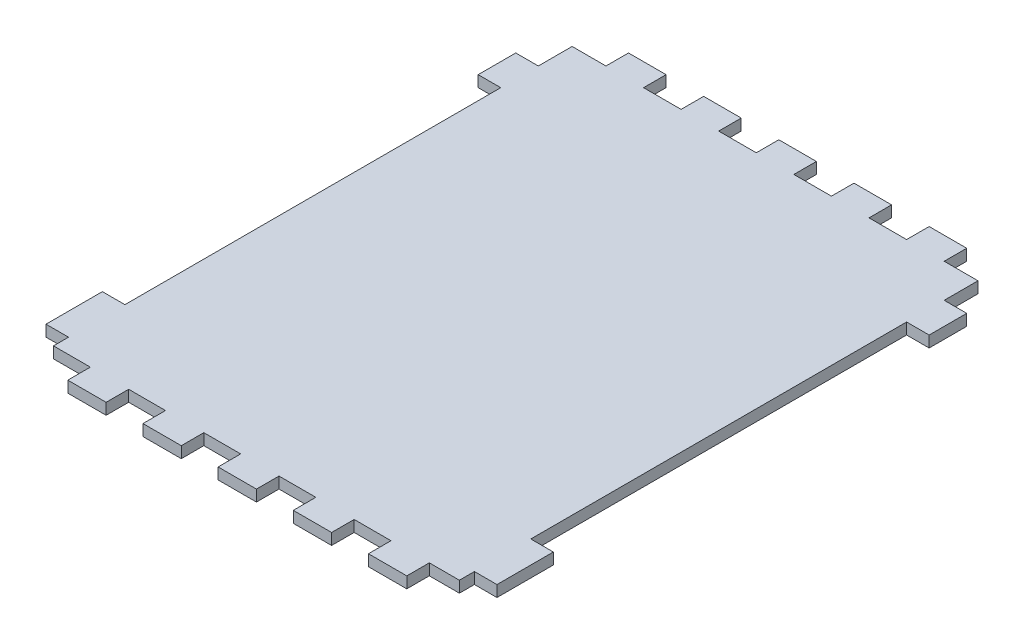
SolidWorks part; units mm, degrees
ref_plane "Спереди" through (0, 0, 0) normal (0, 0, 1) x (1, 0, 0)
ref_plane "Сверху" through (0, 0, 0) normal (0, 1, 0) x (1, 0, 0)
ref_plane "Справа" through (0, 0, 0) normal (1, 0, 0) x (0, 0, -1)
other "Configuration Table"
sketch "Эскиз1" plane through (0, 0, 0) normal (0, 1, 0) x (1, 0, 0)
  line L1 (0, 0) -> (108, 0)
  line L2 (0, 0) -> (0, -138)
  line L3 (0, -138) -> (108, -138)
  line L4 (108, 0) -> (108, -138)
  dimension "D1" = 138
  dimension "D2" = 108
extrude "Бобышка-Вытянуть1" add sketch "Эскиз1" along normal blind 4
sketch "Эскиз3" plane through (0, 0, 0) normal (0, -1, 0) x (1, 0, 0)
  line L1 (0, 138) -> (108, 138)
  line L2 (0, 138) -> (0, 0)
  line L3 (0, 0) -> (108, 0)
  line L4 (108, 138) -> (108, 0)
extrude "Вырез-Вытянуть2" cut sketch "Эскиз3" against normal blind 1
sketch "Эскиз4" plane through (0, 0, 138) normal (0, 0, 1) x (1, 0, 0)
  line L0 (0, 4) -> (108, 4) construction
  line L1 (10, 4) -> (20, 4)
  line L2 (10, 4) -> (10, 1)
  line L3 (10, 1) -> (20, 1)
  line L4 (20, 4) -> (20, 1)
  line L5 (108, 1) -> (0, 1) construction
  line L6 (0, 4) -> (0, 1) construction
  line L7 (30, 4) -> (30, 1)
  line L8 (30, 4) -> (40, 4)
  line L9 (40, 4) -> (40, 1)
  line L10 (30, 1) -> (40, 1)
  line L11 (50, 4) -> (50, 1)
  line L12 (50, 4) -> (60, 4)
  line L13 (60, 4) -> (60, 1)
  line L14 (50, 1) -> (60, 1)
  line L15 (70, 4) -> (70, 1)
  line L16 (70, 4) -> (80, 4)
  line L17 (80, 4) -> (80, 1)
  line L18 (70, 1) -> (80, 1)
  line L19 (90, 4) -> (90, 1)
  line L20 (90, 4) -> (100, 4)
  line L21 (100, 4) -> (100, 1)
  line L22 (90, 1) -> (100, 1)
  dimension "D1" = 10
  dimension "D2" = 10
  dimension "D3" = 5
extrude "Бобышка-Вытянуть2" add sketch "Эскиз4" along normal blind 6
sketch "Эскиз5" plane through (0, 0, 0) normal (-1, 0, 0) x (0, 0, 1)
  line L0 (0, 4) -> (138, 4) construction
  line L1 (9, 4) -> (19, 4)
  line L2 (9, 4) -> (9, 1)
  line L3 (9, 1) -> (19, 1)
  line L4 (19, 4) -> (19, 1)
  line L5 (138, 1) -> (0, 1) construction
  line L6 (0, 4) -> (0, 1) construction
  line L7 (119, 4) -> (134, 4)
  line L8 (119, 4) -> (119, 1)
  line L9 (119, 1) -> (134, 1)
  line L10 (134, 4) -> (134, 1)
  line L11 (138, 4) -> (138, 1) construction
  dimension "D1" = 10
  dimension "D2" = 9
  dimension "D3" = 15
  dimension "D4" = 4
extrude "Бобышка-Вытянуть3" add sketch "Эскиз5" along normal blind 6
sketch "Эскиз6" plane through (108, 0, 0) normal (1, 0, 0) x (0, 0, -1)
  line L0 (-138, 4) -> (0, 4) construction
  line L1 (-134, 4) -> (-119, 4)
  line L2 (-134, 4) -> (-134, 1)
  line L3 (-134, 1) -> (-119, 1)
  line L4 (-119, 4) -> (-119, 1)
  line L5 (0, 1) -> (-138, 1) construction
  line L6 (-138, 4) -> (-138, 1) construction
  line L7 (-19, 4) -> (-9, 4)
  line L8 (-19, 4) -> (-19, 1)
  line L9 (-19, 1) -> (-9, 1)
  line L10 (-9, 4) -> (-9, 1)
  line L11 (0, 4) -> (0, 1) construction
  dimension "D1" = 15
  dimension "D2" = 4
  dimension "D3" = 10
  dimension "D4" = 9
extrude "Бобышка-Вытянуть4" add sketch "Эскиз6" along normal blind 6
sketch "Эскиз7" plane through (0, 0, 0) normal (0, 0, -1) x (-1, 0, 0)
  line L0 (-108, 4) -> (0, 4) construction
  line L1 (-99, 4) -> (-89, 4)
  line L2 (-99, 4) -> (-99, 1)
  line L3 (-99, 1) -> (-89, 1)
  line L4 (-89, 4) -> (-89, 1)
  line L5 (0, 1) -> (-108, 1) construction
  line L6 (-79, 4) -> (-79, 1)
  line L7 (-79, 4) -> (-69, 4)
  line L8 (-69, 4) -> (-69, 1)
  line L9 (-79, 1) -> (-69, 1)
  line L10 (-59, 4) -> (-59, 1)
  line L11 (-59, 4) -> (-49, 4)
  line L12 (-49, 4) -> (-49, 1)
  line L13 (-59, 1) -> (-49, 1)
  line L14 (-39, 4) -> (-39, 1)
  line L15 (-39, 4) -> (-29, 4)
  line L16 (-29, 4) -> (-29, 1)
  line L17 (-39, 1) -> (-29, 1)
  line L18 (-19, 4) -> (-19, 1)
  line L19 (-19, 4) -> (-9, 4)
  line L20 (-9, 4) -> (-9, 1)
  line L21 (-19, 1) -> (-9, 1)
  line L22 (-108, 4) -> (-108, 1) construction
  dimension "D1" = 10
  dimension "D3" = 9
  dimension "D2" = 5
extrude "Бобышка-Вытянуть5" add sketch "Эскиз7" along normal blind 6
sketch "Эскиз8" plane through (10, 0, 0) normal (-1, 0, 0) x (0, 0, 1)
  line L1 (138, 4) -> (144, 4)
  line L2 (138, 4) -> (138, 1)
  line L3 (138, 1) -> (144, 1)
  line L4 (144, 4) -> (144, 1)
extrude "Бобышка-Вытянуть6" add sketch "Эскиз8" along normal blind 0.2
sketch "Эскиз9" plane through (30, 0, 0) normal (-1, 0, 0) x (0, 0, 1)
  line L1 (138, 4) -> (144, 4)
  line L2 (138, 4) -> (138, 1)
  line L3 (138, 1) -> (144, 1)
  line L4 (144, 4) -> (144, 1)
extrude "Бобышка-Вытянуть7" add sketch "Эскиз9" along normal blind 0.2
sketch "Эскиз10" plane through (50, 0, 0) normal (-1, 0, 0) x (0, 0, 1)
  line L1 (138, 4) -> (144, 4)
  line L2 (138, 4) -> (138, 1)
  line L3 (138, 1) -> (144, 1)
  line L4 (144, 4) -> (144, 1)
extrude "Бобышка-Вытянуть8" add sketch "Эскиз10" along normal blind 0.2
sketch "Эскиз11" plane through (70, 0, 0) normal (-1, 0, 0) x (0, 0, 1)
  line L1 (138, 4) -> (144, 4)
  line L2 (138, 4) -> (138, 1)
  line L3 (138, 1) -> (144, 1)
  line L4 (144, 4) -> (144, 1)
extrude "Бобышка-Вытянуть9" add sketch "Эскиз11" along normal blind 0.2
sketch "Эскиз12" plane through (90, 0, 0) normal (-1, 0, 0) x (0, 0, 1)
  line L1 (138, 4) -> (144, 4)
  line L2 (138, 4) -> (138, 1)
  line L3 (138, 1) -> (144, 1)
  line L4 (144, 4) -> (144, 1)
extrude "Бобышка-Вытянуть10" add sketch "Эскиз12" along normal blind 0.2
